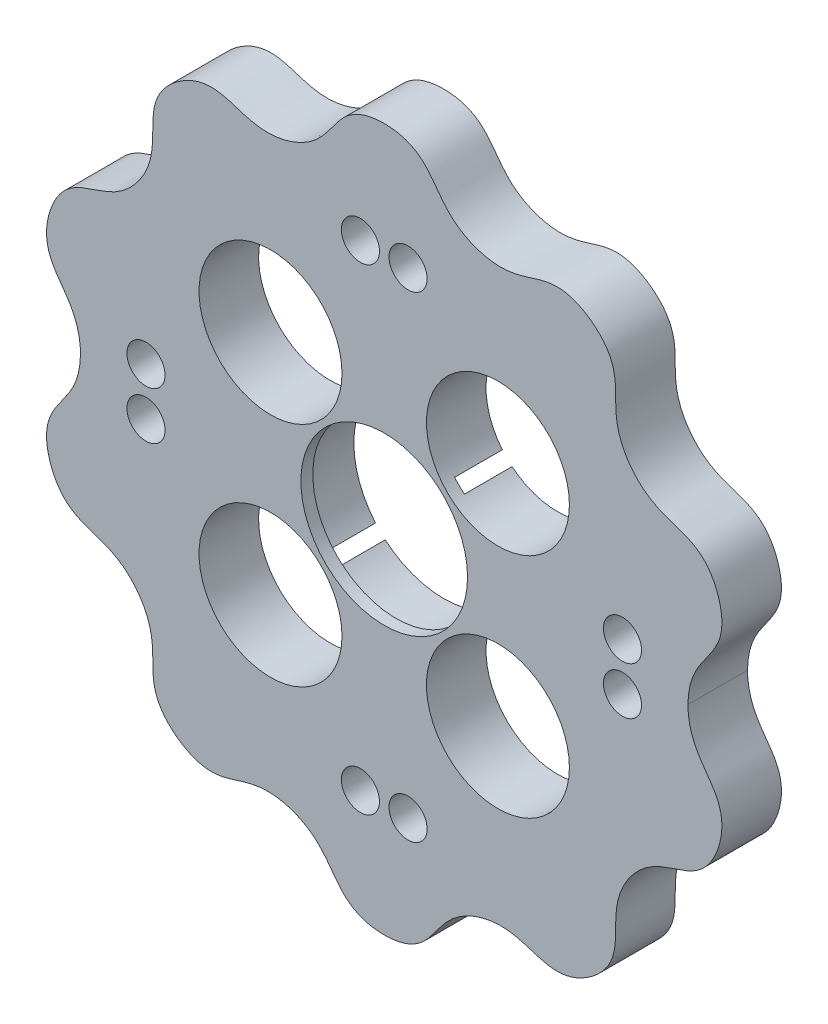
SolidWorks part; units mm, degrees
material "ABS"
ref_plane "Front Plane" through (0, 0, 0) normal (0, 0, 1) x (1, 0, 0)
ref_plane "Top Plane" through (0, 0, 0) normal (0, 1, 0) x (1, 0, 0)
ref_plane "Right Plane" through (0, 0, 0) normal (1, 0, 0) x (0, 0, -1)
ref_plane "Plane1" through (0, 0, 4) normal (0, 0, 1) x (1, 0, 0)
sketch "Sketch3" plane through (0, 0, 4) normal (0, 0, 1) x (1, 0, 0)
  circle A0 centre (2, 0) radius 7.5
  spline S0 degree 5 poles (-23.5, 0) (-23.5, -0.6619) (-23.5985, -1.4561) (-23.8874, -2.4734) (-24.5265, -3.4803) (-25.3239, -4.5428) (-25.7599, -5.1922) (-26.203, -6.107) (-26.3992, -6.9747) (-26.3685, -8.1757) (-26.0322, -9.4106) (-25.4671, -10.5179) (-24.8895, -11.2256) (-23.9802, -11.9083) (-23.1576, -12.2723) (-21.7572, -12.687) (-20.1242, -13.2676) (-18.7699, -14.5833) (-17.7259, -16.1905) (-17.3933, -18.0022) (-17.4393, -19.3418) (-17.4288, -20.3924) (-17.2271, -21.518) (-16.8759, -22.3353) (-16.145, -23.2889) (-15.1471, -24.0902) (-14.0391, -24.6539) (-13.1558, -24.8869) (-12.0189, -24.9048) (-11.1394, -24.7158) (-9.7628, -24.2281) (-8.1004, -23.738) (-6.2314, -24.0063) (-4.442, -24.693) (-3.1081, -25.9632) (-2.3579, -27.074) (-1.7319, -27.9177) (-0.9071, -28.7098) (-0.1425, -29.1646) (1.0093, -29.5065) (2.2876, -29.5682) (3.5153, -29.373) (4.3668, -29.0423) (5.2971, -28.3885) (5.8976, -27.7187) (6.7246, -26.515) (7.7814, -25.1413) (9.4513, -24.2598) (11.3025, -23.7636) (13.1282, -24.0071) (14.3881, -24.4648) (15.3905, -24.7795) (16.5233, -24.9355) (17.4092, -24.854) (18.5419, -24.4536) (19.6124, -23.7522) (20.4909, -22.8726) (20.9855, -22.1045) (21.3538, -21.0288) (21.4458, -20.1339) (21.4074, -18.674) (21.455, -16.9415) (22.2878, -15.2469) (23.4937, -13.7573) (25.1139, -12.8812) (26.4022, -12.5109) (27.3981, -12.1763) (28.4063, -11.6367) (29.0751, -11.05) (29.7562, -10.0602) (30.2099, -8.8636) (30.4037, -7.6356) (30.3523, -6.7236) (30.018, -5.6368) (29.5664, -4.8587) (28.6772, -3.7002) (27.9235, -2.6005) (27.5985, -1.4561) (27.5, -0.6619) (27.5, 0) knots 0.5 0.5 0.5 0.5 0.5 0.5 0.516667 0.52 0.526667 0.53 0.533333 0.536667 0.546667 0.55 0.56 0.563333 0.566667 0.57 0.58 0.583333 0.6 0.61 0.616667 0.626667 0.63 0.633333 0.636667 0.646667 0.65 0.66 0.663333 0.666667 0.67 0.68 0.683333 0.7 0.71 0.716667 0.726667 0.73 0.733333 0.736667 0.746667 0.75 0.76 0.763333 0.766667 0.77 0.78 0.783333 0.8 0.81 0.816667 0.826667 0.83 0.833333 0.836667 0.846667 0.85 0.86 0.863333 0.866667 0.87 0.88 0.883333 0.9 0.91 0.916667 0.926667 0.93 0.933333 0.936667 0.946667 0.95 0.96 0.963333 0.966667 0.97 0.98 0.983333 1 1 1 1 1 1 weights 1 1 1 1 1 1 1 1 1 1 1 1 1 1 1 1 1 1 1 1 1 1 1 1 1 1 1 1 1 1 1 1 1 1 1 1 1 1 1 1 1 1 1 1 1 1 1 1 1 1 1 1 1 1 1 1 1 1 1 1 1 1 1 1 1 1 1 1 1 1 1 1 1 1 1 1 1 1 1 1
  spline S1 degree 5 poles (27.5, 0) (27.5, 0.6619) (27.5985, 1.4561) (27.8874, 2.4734) (28.5265, 3.4803) (29.3239, 4.5428) (29.7599, 5.1922) (30.203, 6.107) (30.3992, 6.9747) (30.3685, 8.1757) (30.0322, 9.4106) (29.4671, 10.5179) (28.8895, 11.2256) (27.9802, 11.9083) (27.1576, 12.2723) (25.7572, 12.687) (24.1242, 13.2676) (22.7699, 14.5833) (21.7259, 16.1905) (21.3933, 18.0022) (21.4393, 19.3418) (21.4288, 20.3924) (21.2271, 21.518) (20.8759, 22.3353) (20.145, 23.2889) (19.1471, 24.0902) (18.0391, 24.6539) (17.1558, 24.8869) (16.0189, 24.9048) (15.1394, 24.7158) (13.7628, 24.2281) (12.1004, 23.738) (10.2314, 24.0063) (8.442, 24.693) (7.1081, 25.9632) (6.3579, 27.074) (5.7319, 27.9177) (4.9071, 28.7098) (4.1425, 29.1646) (2.9907, 29.5065) (1.7124, 29.5682) (0.4847, 29.373) (-0.3668, 29.0423) (-1.2971, 28.3885) (-1.8976, 27.7187) (-2.7246, 26.515) (-3.7814, 25.1413) (-5.4513, 24.2598) (-7.3025, 23.7636) (-9.1282, 24.0071) (-10.3881, 24.4648) (-11.3905, 24.7795) (-12.5233, 24.9355) (-13.4092, 24.854) (-14.5419, 24.4536) (-15.6124, 23.7522) (-16.4909, 22.8726) (-16.9855, 22.1045) (-17.3538, 21.0288) (-17.4458, 20.1339) (-17.4074, 18.674) (-17.455, 16.9415) (-18.2878, 15.2469) (-19.4937, 13.7573) (-21.1139, 12.8812) (-22.4022, 12.5109) (-23.3981, 12.1763) (-24.4063, 11.6367) (-25.0751, 11.05) (-25.7562, 10.0602) (-26.2099, 8.8636) (-26.4037, 7.6356) (-26.3523, 6.7236) (-26.018, 5.6368) (-25.5664, 4.8587) (-24.6772, 3.7002) (-23.9235, 2.6005) (-23.5985, 1.4561) (-23.5, 0.6619) (-23.5, 0) knots 0 0 0 0 0 0 0.016667 0.02 0.026667 0.03 0.033333 0.036667 0.046667 0.05 0.06 0.063333 0.066667 0.07 0.08 0.083333 0.1 0.11 0.116667 0.126667 0.13 0.133333 0.136667 0.146667 0.15 0.16 0.163333 0.166667 0.17 0.18 0.183333 0.2 0.21 0.216667 0.226667 0.23 0.233333 0.236667 0.246667 0.25 0.26 0.263333 0.266667 0.27 0.28 0.283333 0.3 0.31 0.316667 0.326667 0.33 0.333333 0.336667 0.346667 0.35 0.36 0.363333 0.366667 0.37 0.38 0.383333 0.4 0.41 0.416667 0.426667 0.43 0.433333 0.436667 0.446667 0.45 0.46 0.463333 0.466667 0.47 0.48 0.483333 0.5 0.5 0.5 0.5 0.5 0.5 weights 1 1 1 1 1 1 1 1 1 1 1 1 1 1 1 1 1 1 1 1 1 1 1 1 1 1 1 1 1 1 1 1 1 1 1 1 1 1 1 1 1 1 1 1 1 1 1 1 1 1 1 1 1 1 1 1 1 1 1 1 1 1 1 1 1 1 1 1 1 1 1 1 1 1 1 1 1 1 1 1
extrude "CYC Disk" add sketch "Sketch3" along normal blind 5
sketch "Sketch6" plane through (0, 0, 9) normal (0, 0, 1) x (1, 0, 0)
  line L0 (0, 0) -> (2, 0) construction
  circle A1 centre (2, 0) radius 7.55
  dimension "D2" = 15.1
  dimension "D1" = 2
extrude "Cam Bearing" cut sketch "Sketch6" against normal through all
sketch "Sketch8" plane through (0, 0, 9) normal (0, 0, 1) x (1, 0, 0)
  circle A0 centre (2, 0) radius 6.9953
  circle A1 centre (2, 0) radius 7.575
extrude "Cam Bearing Retainer" add sketch "Sketch8" against normal blind 1
sketch "Sketch9" plane through (0, 0, 9) normal (0, 0, 1) x (1, 0, 0)
  line L0 (2, 0) -> (2, 20) construction
  line L2 (4, 20) -> (2, 20)
  line L3 (2, 20) -> (0, 20)
  circle A2 centre (0, 20) radius 1.6
  circle A3 centre (4, 20) radius 1.6
  circle A4 centre (22, -2) radius 1.6
  circle A5 centre (22, 2) radius 1.6
  circle A6 centre (0, -20) radius 1.6
  circle A7 centre (4, -20) radius 1.6
  circle A8 centre (-18, 2) radius 1.6
  circle A9 centre (-18, -2) radius 1.6
  point P23 (2, 0)
  dimension "D3" = 2
  dimension "D4" = 3.2
  dimension "D5" = 3.2
  dimension "D6" = 4
  dimension "D1" = 2
  dimension "D2" = 20
extrude "Positioning Holes" cut sketch "Sketch9" against normal through all
sketch "CYC Ouput Sketch" plane through (2, 0, 4) normal (0, 0, 1) x (1, 0, 0)
  line L1 (9.5459, 9.5459) -> (-9.5459, 9.5459) construction
  line L2 (-9.5459, 9.5459) -> (-9.5459, -9.5459) construction
  line L3 (-9.5459, -9.5459) -> (9.5459, -9.5459) construction
  line L4 (9.5459, -9.5459) -> (9.5459, 9.5459) construction
  circle A0 centre (0, 0) radius 13.5 construction
sketch "Sketch11" plane through (0, 0, 9) normal (0, 0, 1) x (1, 0, 0)
  circle A0 centre (11.5459, 9.5459) radius 6
  circle A1 centre (11.5459, -9.5459) radius 6
  circle A2 centre (-7.5459, -9.5459) radius 6
  circle A3 centre (-7.5459, 9.5459) radius 6
  dimension "D1" = 12
extrude "Output Holes" cut sketch "Sketch11" against normal through all
equation "\"CamBearingOut\"=15.1"
equation "\"D2@Sketch6\"=\"CamBearingOut\""
equation "\"RingPinShaft\"= 5.05"
equation "\"CenterBearingOut\"=32.05"
equation "\"RingPostIn\"=5.15"
